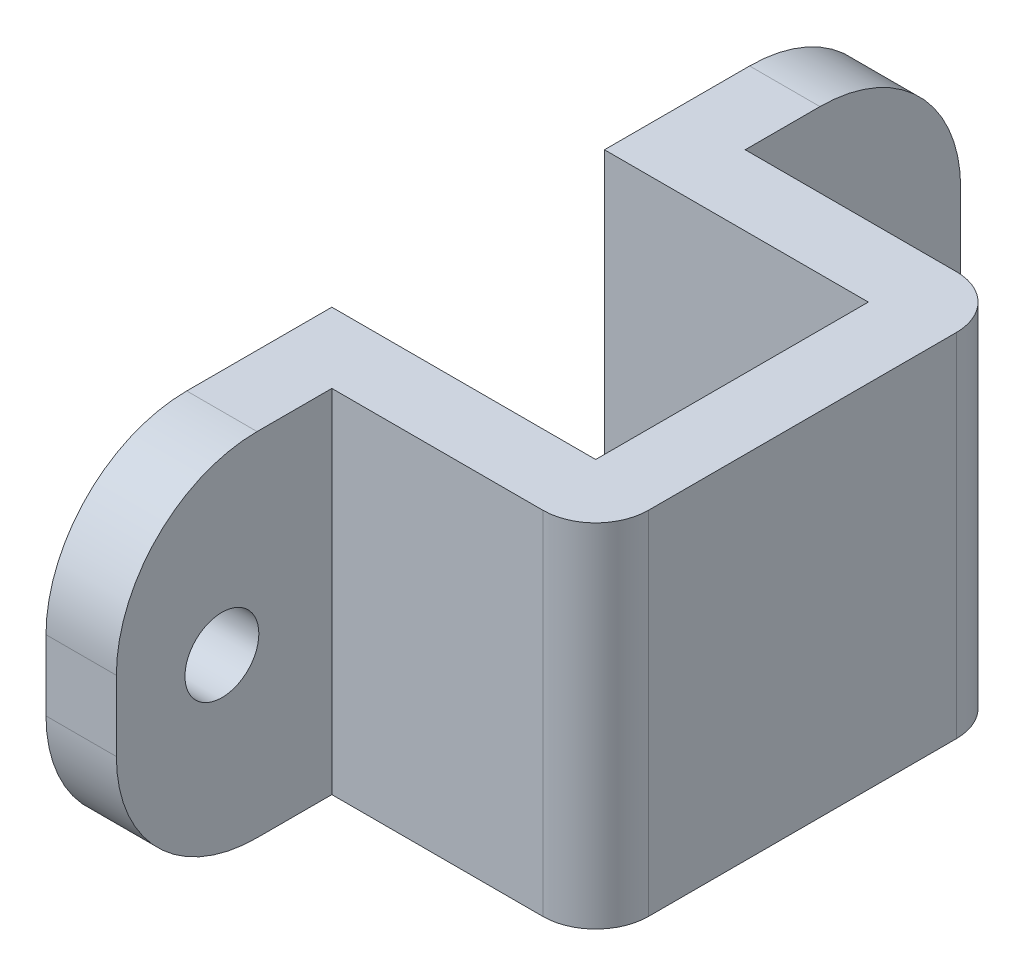
SolidWorks part; units mm, degrees
ref_plane "前视基准面" through (0, 0, 0) normal (0, 0, 1) x (1, 0, 0)
ref_plane "上视基准面" through (0, 0, 0) normal (0, 1, 0) x (1, 0, 0)
ref_plane "右视基准面" through (0, 0, 0) normal (1, 0, 0) x (0, 0, -1)
other "Configuration Table"
sketch "草图2" plane through (0, 0, 0) normal (0, 1, 0) x (1, 0, 0)
  line L0 (0, 0) -> (-19, 0) construction
  line L1 (0, -7.75) -> (0, 7.75)
  line L2 (0, 7.75) -> (-11, 7.75)
  line L3 (-11, 11.75) -> (-11, 20)
  line L5 (-15, 20) -> (-15, 7.75)
  line L7 (-11, -11.75) -> (-11, -20)
  line L8 (0, -7.75) -> (-11, -7.75)
  line L9 (-11, 24) -> (-15, 24)
  line L11 (-11, -24) -> (-15, -24)
  line L13 (4, -11.75) -> (-7, -11.75)
  line L14 (4, -11.75) -> (4, 11.75)
  line L15 (4, 11.75) -> (-7, 11.75)
  line L17 (-15, 20) -> (-15, 24)
  line L18 (-15, -20) -> (-15, -24)
  line L19 (-7, 24) -> (-19, 24) construction
  line L20 (-19, 24) -> (-19, -24) construction
  line L21 (-7, -24) -> (-19, -24) construction
  line L22 (-11, 7.75) -> (-15, 7.75)
  line L23 (-11, -7.75) -> (-15, -7.75)
  line L24 (-15, -7.75) -> (-15, -20)
  line L25 (-15, 20) -> (-15, -20) construction
  line L26 (-11, 20) -> (-11, 24)
  line L27 (-11, -20) -> (-11, -24)
  line L28 (-7, 11.75) -> (-11, 11.75)
  line L29 (-7, -11.75) -> (-11, -11.75)
  line L30 (-11, -7.75) -> (-11, -20) construction
  line L31 (-7, -11.75) -> (-7, -24) construction
  line L32 (-11, -20) -> (-15, -20) construction
  line L33 (-7, 11.75) -> (-7, 24) construction
  line L34 (-11, 7.75) -> (-11, 20) construction
  line L35 (-11, 20) -> (-15, 20) construction
  point P10 (-15, 0)
  point P13 (0, 0)
  dimension "D1" = 40
  dimension "D2" = 15.5
  dimension "D3" = 15
  dimension "D4" = 4
  dimension "D6" = 12.25
  dimension "D5" = 4
extrude "凸台-拉伸1" add sketch "草图2" along normal blind 20
sketch "草图3" plane through (-11, 0, 0) normal (1, 0, 0) x (0, 0, -1)
  line L0 (0, 0) -> (0, 20) construction
  line L1 (-11.75, 0) -> (11.75, 0) construction
  line L2 (-11.75, 20) -> (11.75, 20) construction
  line L3 (-24, 20) -> (-11.75, 20) construction
  line L4 (-24, 20) -> (-24, 0) construction
  circle A0 centre (-18, 10) radius 2.1
  circle A1 centre (18, 10) radius 2.1
  dimension "D3" = 4.2
  dimension "D1" = 10
  dimension "D2" = 6
extrude "切除-拉伸1" cut sketch "草图3" against normal blind 10
fillet "圆角1" radius 8 4 edges at (-13, 20, -24) (-13, 0, -24) (-13, 0, 24) (-13, 20, 24)
fillet "圆角2" radius 3 2 edges at (4, 10, -11.75) (4, 10, 11.75)
